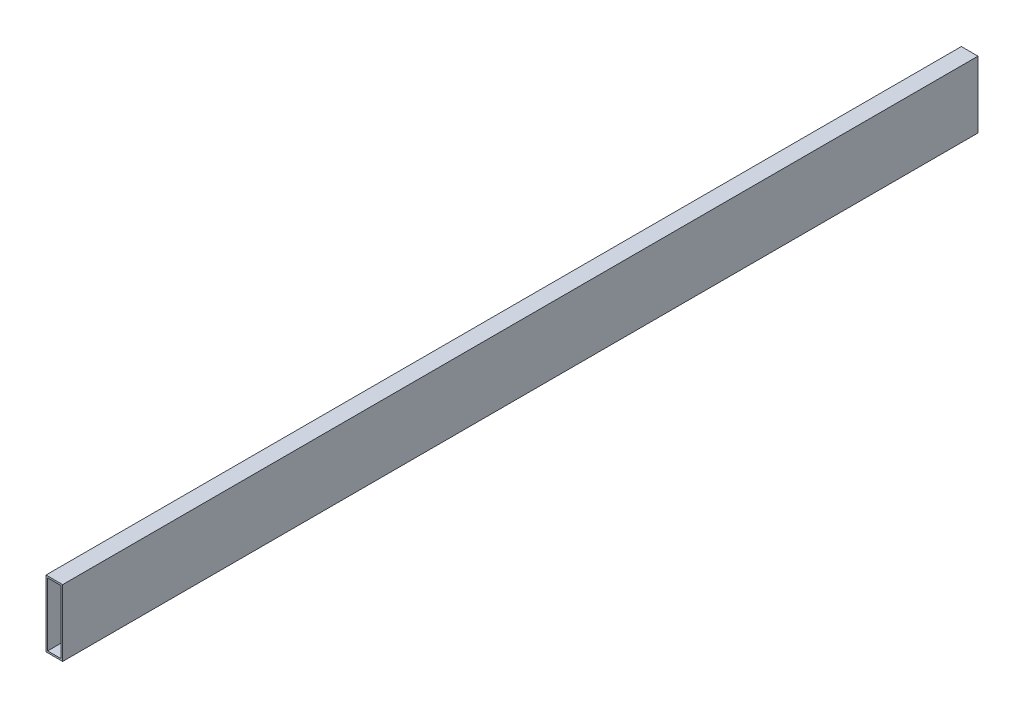
SolidWorks part; units mm, degrees
material "3.0205 (EN-AW 1200)"
ref_plane "前视基准面" through (0, 0, 0) normal (0, 0, 1) x (1, 0, 0)
ref_plane "上视基准面" through (0, 0, 0) normal (0, 1, 0) x (1, 0, 0)
ref_plane "右视基准面" through (0, 0, 0) normal (1, 0, 0) x (0, 0, -1)
sketch "草图1" plane through (0, 0, 0) normal (0, 0, 1) x (1, 0, 0)
  line L1 (-5, 20) -> (5, 20)
  line L2 (-5, 20) -> (-5, -20)
  line L3 (-5, -20) -> (5, -20)
  line L4 (5, 20) -> (5, -20)
  line L5 (-5, 20) -> (5, -20) construction
  line L6 (-5, -20) -> (5, 20) construction
  line L7 (-4, 19) -> (4, 19)
  line L8 (-4, 19) -> (-4, -19)
  line L9 (-4, -19) -> (4, -19)
  line L10 (4, 19) -> (4, -19)
  line L11 (-4, 19) -> (4, -19) construction
  line L12 (-4, -19) -> (4, 19) construction
  point P0 (0, 0)
  point P6 (0, 0)
  dimension "D1" = 10
  dimension "D2" = 40
  dimension "D3" = 38
  dimension "D4" = 8
extrude "凸台-拉伸1" add sketch "草图1" along normal blind 550
